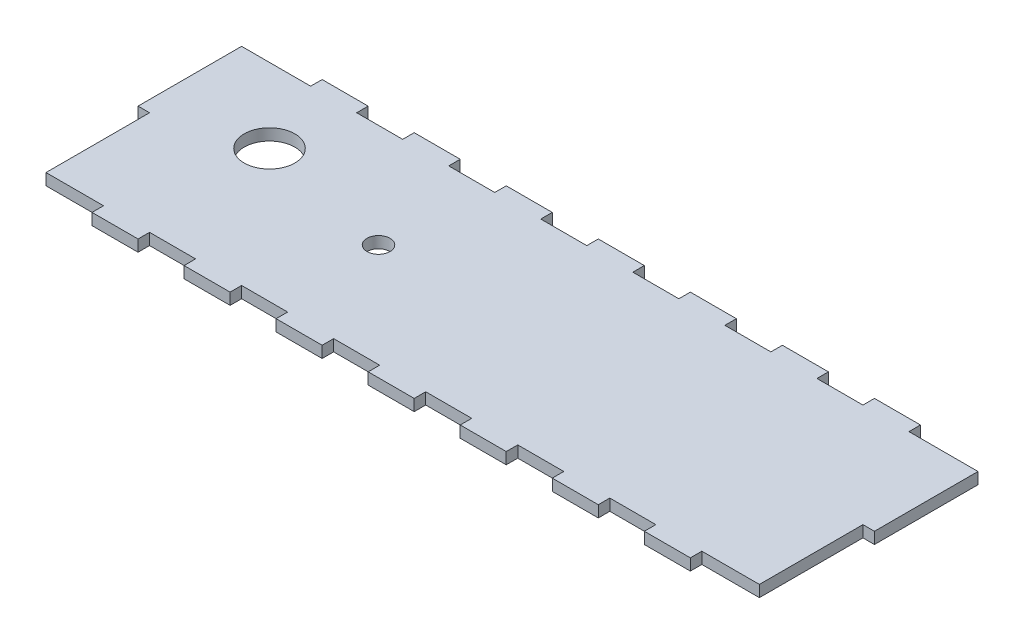
SolidWorks part; units mm, degrees
material "Oak"
ref_plane "Front Plane" through (0, 0, 0) normal (0, 0, 1) x (1, 0, 0)
ref_plane "Top Plane" through (0, 0, 0) normal (0, 1, 0) x (1, 0, 0)
ref_plane "Right Plane" through (0, 0, 0) normal (1, 0, 0) x (0, 0, -1)
sketch "Sketch1" plane through (0, 0, 0) normal (0, 1, 0) x (1, 0, 0)
  line L1 (80, 25) -> (-80, 25)
  line L2 (80, 25) -> (80, -25)
  line L3 (80, -25) -> (-80, -25)
  line L4 (-80, 25) -> (-80, -25)
  line L5 (80, 25) -> (-80, -25) construction
  line L6 (80, -25) -> (-80, 25) construction
  point P0 (0, 0)
  dimension "D1" = 50
  dimension "D2" = 160
extrude "Boss-Extrude1" add sketch "Sketch1" along normal mid plane 2.5
sketch "Sketch2" plane through (0, 1.25, 0) normal (0, 1, 0) x (1, 0, 0)
  line L0 (5, -22.5) -> (-5, -22.5) construction
  line L5 (80, 25) -> (-80, 25) construction
  line L6 (5, 25) -> (-5, 25) construction
  line L11 (5, -22.5) -> (5, -25) construction
  line L24 (5, -25) -> (-5, -25) construction
  line L85 (5, 25) -> (5, 22.5) construction
  line L86 (5, 22.5) -> (-5, 22.5) construction
  line L87 (-5, 25) -> (-5, 22.5) construction
  line L88 (80, -25) -> (80, 25) construction
  line L89 (-5, -22.5) -> (-5, -25) construction
  line L90 (-80, -25) -> (80, -25) construction
  line L115 (25, 22.5) -> (25, 25)
  line L140 (5, 22.5) -> (15, 22.5)
  line L141 (5, 22.5) -> (5, 25)
  line L142 (5, 25) -> (15, 25)
  line L143 (15, 22.5) -> (15, 25)
  line L144 (5, -22.5) -> (15, -22.5)
  line L145 (5, -22.5) -> (5, -25)
  line L146 (5, -25) -> (15, -25)
  line L147 (15, -22.5) -> (15, -25)
  line L148 (25, 22.5) -> (35, 22.5)
  line L149 (35, 22.5) -> (35, 25)
  line L150 (25, 25) -> (35, 25)
  line L151 (25, -22.5) -> (25, -25)
  line L152 (25, -22.5) -> (35, -22.5)
  line L153 (35, -22.5) -> (35, -25)
  line L154 (25, -25) -> (35, -25)
  line L155 (45, 22.5) -> (45, 25)
  line L156 (45, 22.5) -> (55, 22.5)
  line L157 (55, 22.5) -> (55, 25)
  line L158 (45, 25) -> (55, 25)
  line L159 (45, -22.5) -> (45, -25)
  line L160 (45, -22.5) -> (55, -22.5)
  line L161 (55, -22.5) -> (55, -25)
  line L162 (45, -25) -> (55, -25)
  line L163 (5, 22.5) -> (25, 22.5) construction
  line L164 (-15, 22.5) -> (-15, 25)
  line L165 (-15, 22.5) -> (-5, 22.5)
  line L166 (-5, 22.5) -> (-5, 25)
  line L167 (-15, 25) -> (-5, 25)
  line L168 (-15, -22.5) -> (-15, -25)
  line L169 (-15, -22.5) -> (-5, -22.5)
  line L170 (-5, -22.5) -> (-5, -25)
  line L171 (-15, -25) -> (-5, -25)
  line L172 (-35, 22.5) -> (-35, 25)
  line L173 (-35, 22.5) -> (-25, 22.5)
  line L174 (-25, 22.5) -> (-25, 25)
  line L175 (-35, 25) -> (-25, 25)
  line L176 (-35, -22.5) -> (-35, -25)
  line L177 (-35, -22.5) -> (-25, -22.5)
  line L178 (-25, -22.5) -> (-25, -25)
  line L179 (-35, -25) -> (-25, -25)
  line L180 (-55, 22.5) -> (-55, 25)
  line L181 (-55, 22.5) -> (-45, 22.5)
  line L182 (-45, 22.5) -> (-45, 25)
  line L183 (-55, 25) -> (-45, 25)
  line L184 (-55, -22.5) -> (-55, -25)
  line L185 (-55, -22.5) -> (-45, -22.5)
  line L186 (-45, -22.5) -> (-45, -25)
  line L187 (-55, -25) -> (-45, -25)
  line L188 (5, 22.5) -> (-15, 22.5) construction
  line L190 (80, 25) -> (65, 25)
  line L191 (80, 25) -> (80, 22.5)
  line L192 (80, 22.5) -> (65, 22.5)
  line L193 (65, 25) -> (65, 22.5)
  line L194 (80, -25) -> (65, -25)
  line L195 (80, -25) -> (80, -22.5)
  line L196 (80, -22.5) -> (65, -22.5)
  line L197 (65, -25) -> (65, -22.5)
  line L198 (-80, 25) -> (-65, 25)
  line L199 (-80, 25) -> (-80, 22.5)
  line L200 (-80, 22.5) -> (-65, 22.5)
  line L201 (-65, 25) -> (-65, 22.5)
  line L202 (-80, -25) -> (-65, -25)
  line L203 (-80, -25) -> (-80, -22.5)
  line L204 (-80, -22.5) -> (-65, -22.5)
  line L205 (-65, -25) -> (-65, -22.5)
  dimension "D2" = 2.5
  dimension "D1" = 10
  dimension "D3" = 75
  dimension "D4" = 10
  dimension "D5" = 2.5
  dimension "D6" = 75
  dimension "D7" = 10
  dimension "D8" = 10
  dimension "D10" = 20
  dimension "D12" = 20
  dimension "D13" = 2.5
  dimension "D14" = 2.5
  dimension "D15" = 2.5
  dimension "D16" = 2.5
  dimension "D17" = 10
  dimension "D18" = 10
  dimension "D19" = 10
  dimension "D20" = 10
  dimension "D9" = 3
  dimension "D11" = 4
extrude "Cut-Extrude1" cut sketch "Sketch2" against normal blind 4
sketch "Sketch3" plane through (0, 1.25, 0) normal (0, 1, 0) x (1, 0, 0)
  line L0 (0, 0) -> (0, 25) construction
  line L1 (80, 0) -> (77.5, 0)
  line L2 (80, 0) -> (80, -22.5)
  line L3 (80, -22.5) -> (77.5, -22.5)
  line L4 (77.5, 0) -> (77.5, -22.5)
  line L5 (80, -22.5) -> (80, 22.5) construction
  line L6 (5, 25) -> (-5, 25) construction
  line L14 (80, -22.5) -> (65, -22.5) construction
  line L15 (-77.5, 0) -> (-77.5, -22.5)
  line L16 (-80, -22.5) -> (-77.5, -22.5)
  line L17 (-80, 0) -> (-80, -22.5)
  line L18 (-80, 0) -> (-77.5, 0)
  point P5 (78.75, -22.5)
  dimension "D2" = 2.5
  dimension "D3" = 22.5
extrude "Cut-Extrude2" cut sketch "Sketch3" against normal through all
sketch "Sketch4" plane through (0, -1.25, 0) normal (0, -1, 0) x (1, 0, 0)
  circle A0 centre (-57.7529, -6.3187) radius 5.5
  circle A1 centre (-27.7529, 0) radius 2.5
  arc A2 (-58.5529, -6.3187) -> (-56.9529, -6.3187) centre (-57.7529, -6.3187) ccw
  arc A3 (-56.9529, -6.3187) -> (-58.5529, -6.3187) centre (-57.7529, -6.3187) ccw
  arc A4 (-58.5529, -6.3187) -> (-56.9529, -6.3187) centre (-57.7529, -6.3187) ccw
  arc A5 (-56.9529, -6.3187) -> (-58.5529, -6.3187) centre (-57.7529, -6.3187) ccw
  dimension "D2" = 11
  dimension "D4" = 5
  dimension "D3" = 30
  dimension "D1" = 0
extrude "Cut-Extrude4" cut sketch "Sketch4" against normal up to next contours A0 | A1
equation "\"thick\"= 0.25"
equation "\"D2@Sketch3\"=\"thick\""
equation "\"corner\"=2.1"
equation "\"D3@Sketch3\"=( +\"width\" - \"thick\" * 2 ) / 2"
equation "\"D1@Boss-Extrude1\"=\"thick\""
equation "\"length\"= 16"
equation "\"width\"=5"
equation "\"D1@Sketch1\"=\"width\""
equation "\"D2@Sketch1\"=\"length\""
equation "\"hole_length\"=1"
equation "\"D1@Sketch2\"=\"hole_length\""
equation "\"D6@Sketch2\"=\"D3@Sketch2\""
equation "\"D5@Sketch2\"=\"thick\""
equation "\"D4@Sketch2\"=\"hole_length\""
equation "\"D3@Sketch2\"=(\"length\" - 1) / 2"
equation "\"D2@Sketch2\"=\"thick\""
equation "\"D7@Sketch2\"=\"D1@Sketch2\""
equation "\"D8@Sketch2\"=\"D1@Sketch2\""
equation "\"D13@Sketch2\"=\"thick\""
equation "\"D14@Sketch2\"=\"D13@Sketch2\""
equation "\"D15@Sketch2\"=\"D13@Sketch2\""
equation "\"D16@Sketch2\"=\"D15@Sketch2\""
equation "\"D17@Sketch2\"=\"hole_length\""
equation "\"D18@Sketch2\"=\"D17@Sketch2\""
equation "\"D19@Sketch2\"=\"D18@Sketch2\""
equation "\"D20@Sketch2\"=\"D19@Sketch2\""
